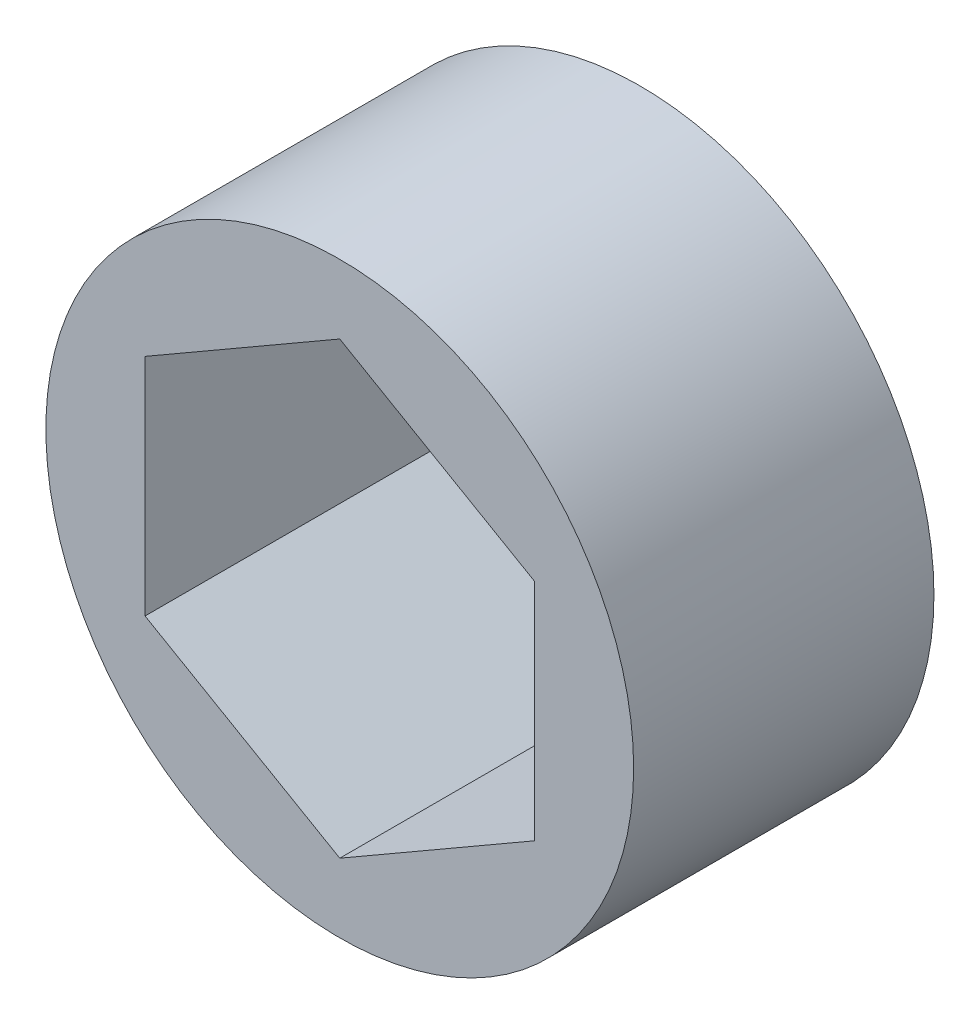
SolidWorks part; units mm, degrees
material "Nylon 101"
ref_plane "Front Plane" through (0, 0, 0) normal (0, 0, 1) x (1, 0, 0)
ref_plane "Top Plane" through (0, 0, 0) normal (0, 1, 0) x (1, 0, 0)
ref_plane "Right Plane" through (0, 0, 0) normal (1, 0, 0) x (0, 0, -1)
sketch "Sketch1" plane through (0, 0, 0) normal (0, 0, 1) x (1, 0, 0)
  line L1 (6.731, 3.8861) -> (0, 7.7723)
  line L2 (0, 7.7723) -> (-6.731, 3.8861)
  line L3 (-6.731, 3.8861) -> (-6.731, -3.8861)
  line L4 (-6.731, -3.8861) -> (0, -7.7723)
  line L5 (0, -7.7723) -> (6.731, -3.8861)
  line L6 (6.731, -3.8861) -> (6.731, 3.8861)
  circle A0 centre (0, 0) radius 6.731 construction
  circle A1 centre (0, 0) radius 10.16
  dimension "D1" = 13.462
  dimension "D2" = 20.32
extrude "Boss-Extrude1" add sketch "Sketch1" along normal blind 10.3815
